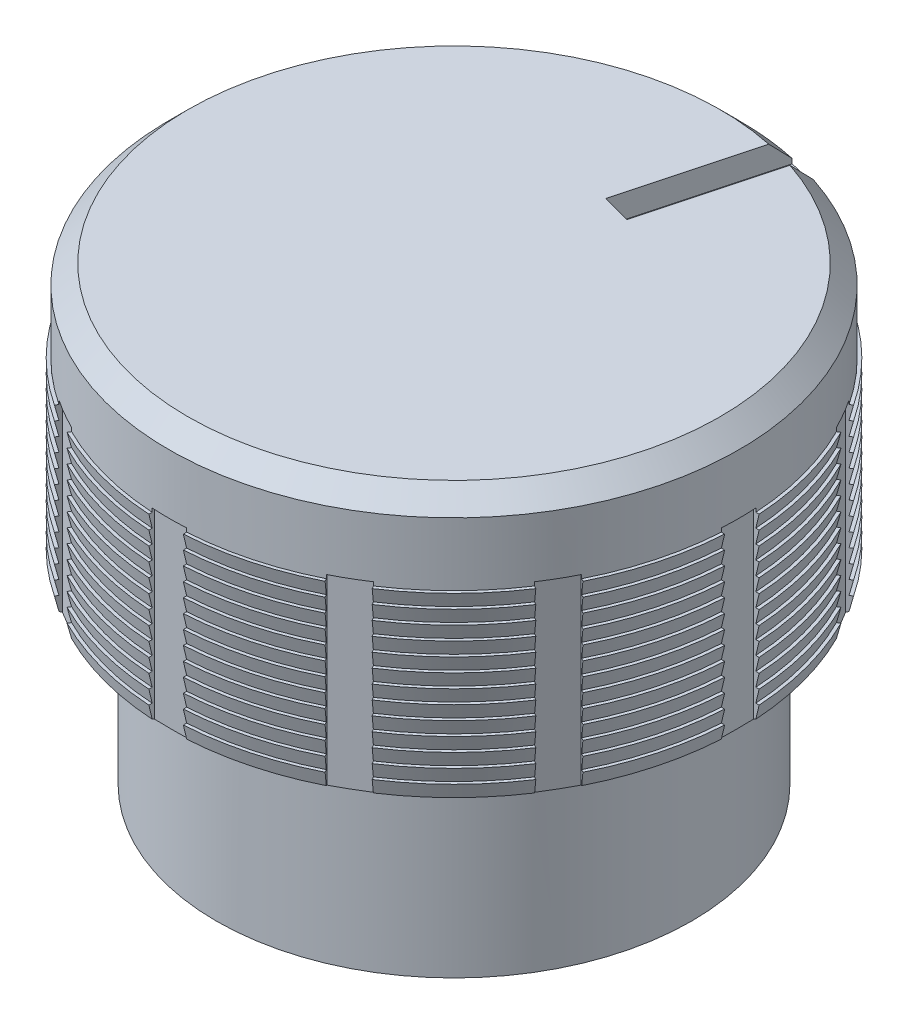
SolidWorks part; units mm, degrees
ref_plane "Спереди" through (0, 0, 0) normal (0, 0, 1) x (1, 0, 0)
ref_plane "Сверху" through (0, 0, 0) normal (0, 1, 0) x (1, 0, 0)
ref_plane "Справа" through (0, 0, 0) normal (1, 0, 0) x (0, 0, -1)
sketch "Эскиз2" plane through (0, 0, 0) normal (0, 0, 1) x (1, 0, 0)
  line L0 (0, 0) -> (0, 78.0521) construction
  line L1 (0, 11.4253) -> (2.6, 11.4253)
  line L3 (5.3814, 2.4253) -> (5, 2.4253)
  line L4 (5, 2.4253) -> (5, 6.4253)
  line L5 (6, 6.9253) -> (6.07, 7.2184)
  line L6 (6, 6.9253) -> (6, 10.4253) construction
  line L7 (6, 6.9253) -> (5, 6.4253)
  line L8 (6, 10.7603) -> (6, 12.4253)
  line L9 (6, 12.4253) -> (0, 12.4253)
  line L10 (0, 12.4253) -> (0, 11.4253)
  line L11 (6, 10.4253) -> (6, 10.7603)
  line L12 (6.07, 7.2184) -> (6, 7.2184)
  line L13 (6.0007, 7.2184) -> (6.07, 7.5084)
  line L14 (6.07, 7.5084) -> (6, 7.5084)
  line L15 (6, 7.5053) -> (6.07, 7.7984)
  line L16 (6.07, 7.7984) -> (6, 7.7984)
  line L17 (6, 7.7953) -> (6.07, 8.0884)
  line L18 (6.07, 8.0884) -> (6, 8.0884)
  line L19 (6, 8.0853) -> (6.07, 8.3784)
  line L20 (6.07, 8.3784) -> (6, 8.3784)
  line L21 (6, 8.3753) -> (6.07, 8.6684)
  line L22 (6.07, 8.6684) -> (6, 8.6684)
  line L23 (6, 8.6653) -> (6.07, 8.9584)
  line L24 (6.07, 8.9584) -> (6, 8.9584)
  line L25 (6, 8.9553) -> (6.07, 9.2484)
  line L26 (6.07, 9.2484) -> (6, 9.2484)
  line L27 (6, 9.2453) -> (6.07, 9.5384)
  line L28 (6.07, 9.5384) -> (6, 9.5384)
  line L29 (6, 9.5353) -> (6.07, 9.8284)
  line L30 (6.07, 9.8284) -> (6, 9.8284)
  line L31 (6, 9.8253) -> (6.07, 10.1184)
  line L32 (6.07, 10.1184) -> (6, 10.1184)
  line L33 (6, 10.1153) -> (6.07, 10.4084)
  line L34 (6.07, 10.4084) -> (6, 10.4084)
  line L35 (6, 10.4053) -> (6.07, 10.6984)
  line L36 (6.07, 10.6984) -> (6, 10.6984)
  line L37 (6, 10.6953) -> (6.07, 10.9884)
  line L38 (6.07, 10.9884) -> (6, 10.9884)
  line L39 (6, 10.9853) -> (6.07, 11.2784)
  line L40 (6.07, 11.2784) -> (6, 11.2784)
  line L41 (6, 11.2753) -> (6.07, 11.5684)
  line L42 (6.07, 11.5684) -> (6, 11.5684)
  line L43 (6, 11.5653) -> (6.07, 11.8584)
  line L44 (6.07, 11.8584) -> (6, 11.8584)
  line L45 (6, 11.8553) -> (6.07, 12.1484)
  line L46 (6.07, 12.1484) -> (6, 12.1484)
  line L47 (6, 12.1453) -> (6.07, 12.4384)
  line L48 (6.07, 12.4384) -> (6, 12.4384)
  line L49 (6, 12.4353) -> (6.07, 12.7284)
  line L50 (6.07, 12.7284) -> (6, 12.7284)
  line L51 (6, 12.7253) -> (6.07, 13.0184)
  line L52 (6.07, 13.0184) -> (6, 13.0184)
  line L53 (6, 13.0153) -> (6.07, 13.3084)
  line L54 (6.07, 13.3084) -> (6, 13.3084)
  line L55 (6, 13.3053) -> (6.07, 13.5984)
  line L56 (6.07, 13.5984) -> (6, 13.5984)
  line L57 (6, 13.5953) -> (6.07, 13.8884)
  line L58 (6.07, 13.8884) -> (6, 13.8884)
  line L59 (6, 13.8853) -> (6.07, 14.1784)
  line L60 (6.07, 14.1784) -> (6, 14.1784)
  line L61 (6, 14.1753) -> (6.07, 14.4684)
  line L62 (6.07, 14.4684) -> (6, 14.4684)
  line L63 (6, 14.4653) -> (6.07, 14.7584)
  line L64 (6.07, 14.7584) -> (6, 14.7584)
  line L65 (6, 14.7553) -> (6.07, 15.0484)
  line L66 (6.07, 15.0484) -> (6, 15.0484)
  line L67 (6, 15.0453) -> (6.07, 15.3384)
  line L68 (6.07, 15.3384) -> (6, 15.3384)
  line L69 (6, 15.3353) -> (6.07, 15.6284)
  line L70 (6.07, 15.6284) -> (6, 15.6284)
  line L71 (6, 15.6253) -> (6.07, 15.9184)
  line L72 (6.07, 15.9184) -> (6, 15.9184)
  line L73 (6, 15.9153) -> (6.07, 16.2084)
  line L74 (6.07, 16.2084) -> (6, 16.2084)
  line L75 (6, 10.4253) -> (6, 16.2084)
  line L76 (3.7247, 2.9313) -> (5.3814, 2.9313)
  line L77 (5.3814, 2.9313) -> (5.3814, 2.4253)
  line L78 (3.7247, 2.9313) -> (3.7247, 6.4253)
  line L79 (3.7247, 6.4253) -> (2.6, 6.4253)
  line L80 (2.6, 6.4253) -> (2.6, 11.4253)
  dimension "D1" = 10
  dimension "D3" = 6
  dimension "D4" = 5
  dimension "D5" = 6
  dimension "D6" = 1
  dimension "D7" = 2
  dimension "D8" = 4
  dimension "D9" = 1.6651
  dimension "D10" = 4.5
  dimension "D11" = 0.07
  dimension "D13" = 2.6
  dimension "D12" = 32
revolve "Повернуть1" add sketch "Эскиз2" angle 360 about L0
sketch "Эскиз3" plane through (0, 12.4253, 0) normal (0, 1, 0) x (1, 0, 0)
  line L0 (0, 0) -> (0, 8.9015) construction
  line L1 (0.3627, 6.9563) -> (-0.3627, 6.9563)
  line L2 (-0.3627, 6.9563) -> (-0.3627, 5.9366)
  line L3 (-0.3627, 5.9366) -> (0.3627, 5.9366)
  line L4 (0.3627, 6.9563) -> (0.3627, 5.9366)
  line L5 (3.7923, 5.843) -> (3.164, 6.2057)
  line L6 (3.164, 6.2057) -> (2.6542, 5.3226)
  line L7 (3.7923, 5.843) -> (3.2824, 4.9599)
  line L8 (2.6542, 5.3226) -> (3.2824, 4.9599)
  line L9 (6.2057, 3.164) -> (5.843, 3.7923)
  line L10 (5.843, 3.7923) -> (4.9599, 3.2824)
  line L11 (6.2057, 3.164) -> (5.3226, 2.6542)
  line L12 (4.9599, 3.2824) -> (5.3226, 2.6542)
  line L13 (6.9563, -0.3627) -> (6.9563, 0.3627)
  line L14 (6.9563, 0.3627) -> (5.9366, 0.3627)
  line L15 (6.9563, -0.3627) -> (5.9366, -0.3627)
  line L16 (5.9366, 0.3627) -> (5.9366, -0.3627)
  line L17 (5.843, -3.7923) -> (6.2057, -3.164)
  line L18 (6.2057, -3.164) -> (5.3226, -2.6542)
  line L19 (5.843, -3.7923) -> (4.9599, -3.2824)
  line L20 (5.3226, -2.6542) -> (4.9599, -3.2824)
  line L21 (3.164, -6.2057) -> (3.7923, -5.843)
  line L22 (3.7923, -5.843) -> (3.2824, -4.9599)
  line L23 (3.164, -6.2057) -> (2.6542, -5.3226)
  line L24 (3.2824, -4.9599) -> (2.6542, -5.3226)
  line L25 (-0.3627, -6.9563) -> (0.3627, -6.9563)
  line L26 (0.3627, -6.9563) -> (0.3627, -5.9366)
  line L27 (-0.3627, -6.9563) -> (-0.3627, -5.9366)
  line L28 (0.3627, -5.9366) -> (-0.3627, -5.9366)
  line L29 (-3.7923, -5.843) -> (-3.164, -6.2057)
  line L30 (-3.164, -6.2057) -> (-2.6542, -5.3226)
  line L31 (-3.7923, -5.843) -> (-3.2824, -4.9599)
  line L32 (-2.6542, -5.3226) -> (-3.2824, -4.9599)
  line L33 (-6.2057, -3.164) -> (-5.843, -3.7923)
  line L34 (-5.843, -3.7923) -> (-4.9599, -3.2824)
  line L35 (-6.2057, -3.164) -> (-5.3226, -2.6542)
  line L36 (-4.9599, -3.2824) -> (-5.3226, -2.6542)
  line L37 (-6.9563, 0.3627) -> (-6.9563, -0.3627)
  line L38 (-6.9563, -0.3627) -> (-5.9366, -0.3627)
  line L39 (-6.9563, 0.3627) -> (-5.9366, 0.3627)
  line L40 (-5.9366, -0.3627) -> (-5.9366, 0.3627)
  line L41 (-5.843, 3.7923) -> (-6.2057, 3.164)
  line L42 (-6.2057, 3.164) -> (-5.3226, 2.6542)
  line L43 (-5.843, 3.7923) -> (-4.9599, 3.2824)
  line L44 (-5.3226, 2.6542) -> (-4.9599, 3.2824)
  line L45 (-3.164, 6.2057) -> (-3.7923, 5.843)
  line L46 (-3.7923, 5.843) -> (-3.2824, 4.9599)
  line L47 (-3.164, 6.2057) -> (-2.6542, 5.3226)
  line L48 (-3.2824, 4.9599) -> (-2.6542, 5.3226)
  point P8 (0, 5.9366)
  point P9 (0, 6.9563)
  point P56 (0, 0)
  dimension "D1" = 12
extrude "Вырез-Вытянуть1" cut sketch "Эскиз3" against normal blind 10.35 from offset 1.65 offset against normal yes
chamfer "Фаска1" distance 0.4 angle 45 1 edges at (0, 12.4253, -6)
sketch "Эскиз4" plane through (0, 12.4253, 0) normal (0, 1, 0) x (1, 0, 0)
  line L0 (0, 0) -> (1.4235, 5.3126) construction
  line L1 (1.0248, 2.6136) -> (0.4193, 2.7758)
  line L2 (1.296, 6.0478) -> (1.9016, 5.8856)
  line L3 (1.296, 6.0478) -> (0.4193, 2.7758)
  line L4 (1.9016, 5.8856) -> (1.0248, 2.6136)
  circle A0 centre (0, 0) radius 6.5 construction
  point P10 (0.722, 2.6947)
  point P12 (1.5988, 5.9667)
extrude "Вырез-Вытянуть2" cut sketch "Эскиз4" against normal blind 0.5
sketch "Эскиз5" plane through (0, 6.4253, 0) normal (0, -1, 0) x (1, 0, 0)
  line L0 (0, 0) -> (0, 3.7247) construction
  line L1 (0.3562, 2.8136) -> (-0.3562, 2.8136)
  line L2 (-0.3562, 2.8136) -> (-0.5052, 2.5504)
  line L3 (-0.5052, 2.5504) -> (0, 2.4381)
  line L4 (0.5052, 2.5504) -> (0, 2.4381)
  line L5 (0.3562, 2.8136) -> (0.5052, 2.5504)
  line L6 (1.6229, 2.3258) -> (0.9922, 2.6568)
  line L7 (0.9922, 2.6568) -> (0.7379, 2.4931)
  line L8 (0.7379, 2.4931) -> (1.1331, 2.1588)
  line L9 (1.6326, 2.0235) -> (1.1331, 2.1588)
  line L10 (1.6229, 2.3258) -> (1.6326, 2.0235)
  line L11 (2.5179, 1.3052) -> (2.1132, 1.8914)
  line L12 (2.1132, 1.8914) -> (1.812, 1.8646)
  line L13 (1.812, 1.8646) -> (2.0065, 1.385)
  line L14 (2.386, 1.0331) -> (2.0065, 1.385)
  line L15 (2.5179, 1.3052) -> (2.386, 1.0331)
  line L16 (2.836, -0.0144) -> (2.7501, 0.6927)
  line L17 (2.7501, 0.6927) -> (2.471, 0.8089)
  line L18 (2.471, 0.8089) -> (2.4203, 0.2939)
  line L19 (2.5927, -0.1941) -> (2.4203, 0.2939)
  line L20 (2.836, -0.0144) -> (2.5927, -0.1941)
  line L21 (2.5044, -1.3307) -> (2.7571, -0.6647)
  line L22 (2.7571, -0.6647) -> (2.5639, -0.432)
  line L23 (2.5639, -0.432) -> (2.2797, -0.8646)
  line L24 (2.2056, -1.3768) -> (2.2797, -0.8646)
  line L25 (2.5044, -1.3307) -> (2.2056, -1.3768)
  line L26 (1.5992, -2.3422) -> (2.1324, -1.8698)
  line L27 (2.1324, -1.8698) -> (2.0694, -1.574)
  line L28 (2.0694, -1.574) -> (1.6168, -1.825)
  line L29 (1.3131, -2.244) -> (1.6168, -1.825)
  line L30 (1.5992, -2.3422) -> (1.3131, -2.244)
  line L31 (0.3275, -2.8171) -> (1.0192, -2.6466)
  line L32 (1.0192, -2.6466) -> (1.1009, -2.3554)
  line L33 (1.1009, -2.3554) -> (0.5835, -2.3673)
  line L34 (0.1198, -2.5972) -> (0.5835, -2.3673)
  line L35 (0.3275, -2.8171) -> (0.1198, -2.5972)
  line L36 (-1.0192, -2.6466) -> (-0.3275, -2.8171)
  line L37 (-0.3275, -2.8171) -> (-0.1198, -2.5972)
  line L38 (-0.1198, -2.5972) -> (-0.5835, -2.3673)
  line L39 (-1.1009, -2.3554) -> (-0.5835, -2.3673)
  line L40 (-1.0192, -2.6466) -> (-1.1009, -2.3554)
  line L41 (-2.1324, -1.8698) -> (-1.5992, -2.3422)
  line L42 (-1.5992, -2.3422) -> (-1.3131, -2.244)
  line L43 (-1.3131, -2.244) -> (-1.6168, -1.825)
  line L44 (-2.0694, -1.574) -> (-1.6168, -1.825)
  line L45 (-2.1324, -1.8698) -> (-2.0694, -1.574)
  line L46 (-2.7571, -0.6647) -> (-2.5044, -1.3307)
  line L47 (-2.5044, -1.3307) -> (-2.2056, -1.3768)
  line L48 (-2.2056, -1.3768) -> (-2.2797, -0.8646)
  line L49 (-2.5639, -0.432) -> (-2.2797, -0.8646)
  line L50 (-2.7571, -0.6647) -> (-2.5639, -0.432)
  line L51 (-2.7501, 0.6927) -> (-2.836, -0.0144)
  line L52 (-2.836, -0.0144) -> (-2.5927, -0.1941)
  line L53 (-2.5927, -0.1941) -> (-2.4203, 0.2939)
  line L54 (-2.471, 0.8089) -> (-2.4203, 0.2939)
  line L55 (-2.7501, 0.6927) -> (-2.471, 0.8089)
  line L56 (-2.1132, 1.8914) -> (-2.5179, 1.3052)
  line L57 (-2.5179, 1.3052) -> (-2.386, 1.0331)
  line L58 (-2.386, 1.0331) -> (-2.0065, 1.385)
  line L59 (-1.812, 1.8646) -> (-2.0065, 1.385)
  line L60 (-2.1132, 1.8914) -> (-1.812, 1.8646)
  line L61 (-0.9922, 2.6568) -> (-1.6229, 2.3258)
  line L62 (-1.6229, 2.3258) -> (-1.6326, 2.0235)
  line L63 (-1.6326, 2.0235) -> (-1.1331, 2.1588)
  line L64 (-0.7379, 2.4931) -> (-1.1331, 2.1588)
  line L65 (-0.9922, 2.6568) -> (-0.7379, 2.4931)
  circle A0 centre (0, 0) radius 3.7247 construction
  circle A1 centre (0, 0) radius 2.6 construction
  point P14 (0, 2.8136)
  point P22 (1.3075, 2.4913)
  point P28 (2.3155, 1.5983)
  point P34 (2.7931, 0.3391)
  point P40 (2.6308, -0.9977)
  point P46 (1.8658, -2.106)
  point P52 (0.6733, -2.7318)
  point P58 (-0.6733, -2.7318)
  point P64 (-1.8658, -2.106)
  point P70 (-2.6308, -0.9977)
  point P76 (-2.7931, 0.3391)
  point P82 (-2.3155, 1.5983)
  point P88 (-1.3075, 2.4913)
  point P89 (0, 0)
  dimension "D1" = 13
extrude "Вырез-Вытянуть3" cut sketch "Эскиз5" against normal up to surface (5 mm away) up to face at (0, 11.4253, -2.6)
